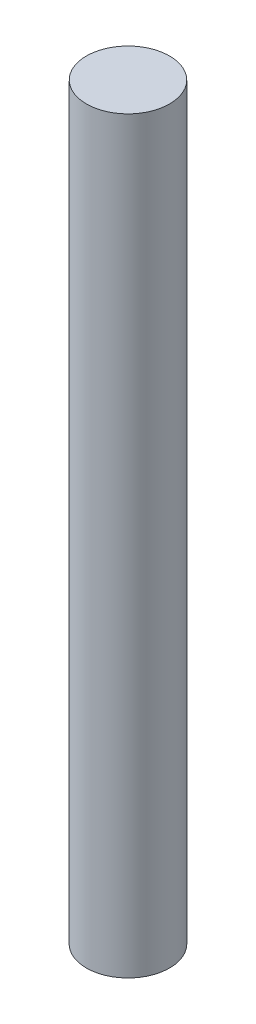
SolidWorks part; units mm, degrees
ref_plane "Front Plane" through (0, 0, 0) normal (0, 0, 1) x (1, 0, 0)
ref_plane "Top Plane" through (0, 0, 0) normal (0, 1, 0) x (1, 0, 0)
ref_plane "Right Plane" through (0, 0, 0) normal (1, 0, 0) x (0, 0, -1)
sketch "Sketch1" plane through (0, 0, 0) normal (0, 1, 0) x (1, 0, 0)
  circle A0 centre (0, 0) radius 1.27
  dimension "D1" = 2.54
extrude "Boss-Extrude1" add sketch "Sketch1" along normal blind 22.86
